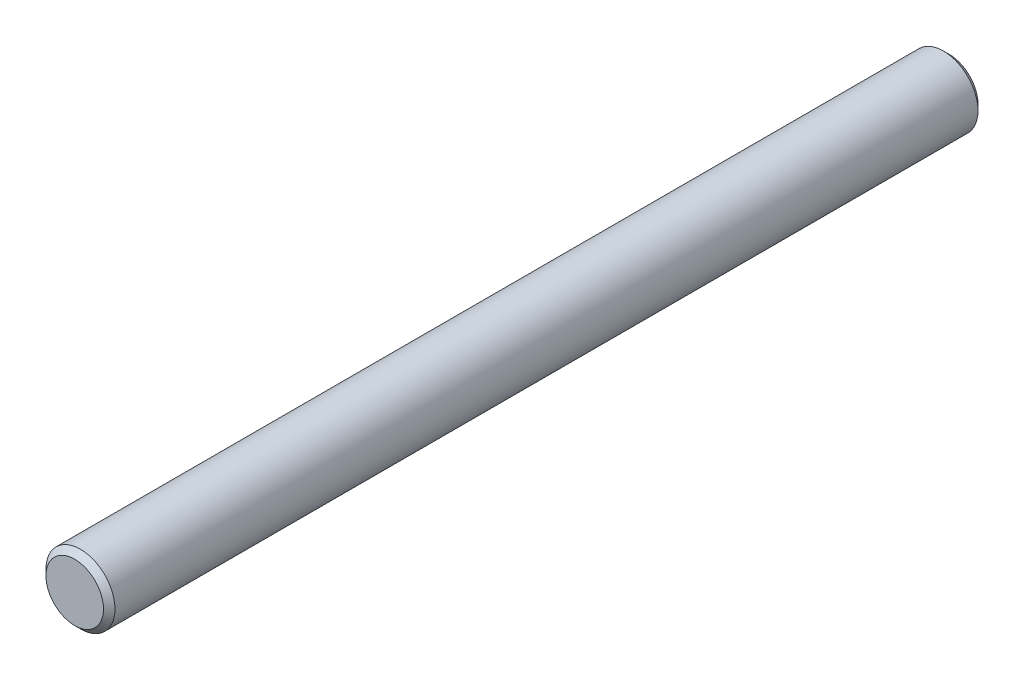
SolidWorks part; units mm, degrees
ref_plane "Plan de face" through (0, 0, 0) normal (0, 0, 1) x (1, 0, 0)
ref_plane "Plan de dessus" through (0, 0, 0) normal (0, 1, 0) x (1, 0, 0)
ref_plane "Plan de droite" through (0, 0, 0) normal (1, 0, 0) x (0, 0, -1)
sketch "Esquisse1" plane through (0, 0, 0) normal (0, 0, 1) x (1, 0, 0)
  circle A0 centre (0, 0) radius 1.5
  dimension "D1" = 3
extrude "Boss.-Extru.1" add sketch "Esquisse1" along normal blind 38
chamfer "Chanfrein1" distance 0.25 angle 45 2 edges at (1.5, 0, 0) (1.5, 0, 38)
